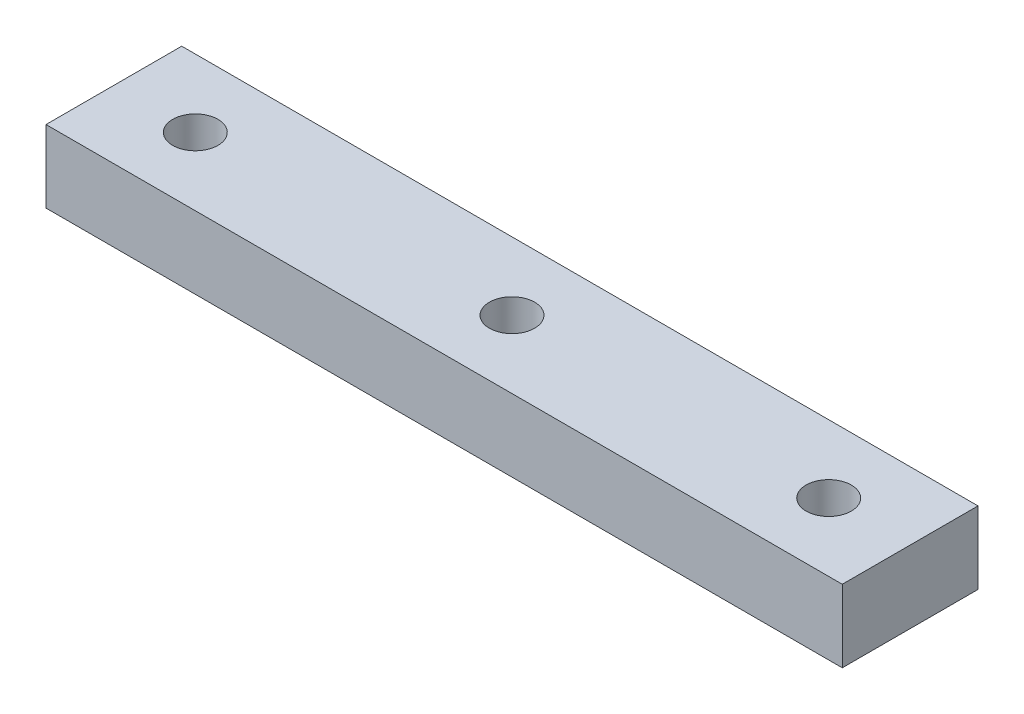
SolidWorks part; units mm, degrees
material "6061"
ref_plane "前视" through (0, 0, 0) normal (0, 0, 1) x (1, 0, 0)
ref_plane "上视" through (0, 0, 0) normal (0, 1, 0) x (1, 0, 0)
ref_plane "右视" through (0, 0, 0) normal (1, 0, 0) x (0, 0, -1)
sketch "草图2" plane through (0, 0, 0) normal (0, 0, 1) x (1, 0, 0)
  line L1 (-44, -4) -> (44, -4)
  line L2 (-44, -4) -> (-44, 4)
  line L3 (-44, 4) -> (44, 4)
  line L4 (44, -4) -> (44, 4)
  line L5 (-44, -4) -> (44, 4) construction
  line L6 (-44, 4) -> (44, -4) construction
  point P0 (0, 0)
  dimension "D1" = 88
  dimension "D2" = 8
extrude "凸台-拉伸1" add sketch "草图2" along normal mid plane 15
hole_wizard "M6 螺纹孔1" positions "草图4" profile "草图3" tap size "M6" standard "Gb" end condition through all
sketch "草图4" plane through (0, -4, 0) normal (0, -1, 0) x (-1, 0, 0)
  line L0 (44, 0) -> (0, 0) construction
  line L1 (44, -7.5) -> (44, 7.5) construction
  line L2 (0, 0) -> (0, -7.5) construction
  line L3 (44, -7.5) -> (-44, -7.5) construction
  point P0 (35, 0)
  point P15 (-35, 0)
  point P18 (0, 0)
  dimension "D1" = 70
sketch "草图3" plane through (-35, -4, 0) normal (1, 0, 0) x (0, 0, -1)
  line L0 (0, 0) -> (0, 8)
  line L1 (0, 8) -> (2.5, 8)
  line L2 (2.5, 8) -> (2.5, 0)
  line L5 (2.5, 0) -> (0, 0)
  line L11 (0, -6.35) -> (0, 107.95) construction
  dimension "通孔螺纹孔钻头直径" = 5
  dimension "通孔螺纹孔钻头深度" = 8
cosmetic thread "孔螺蚊线1"
cosmetic thread "孔螺蚊线2"
cosmetic thread "孔螺蚊线3"
